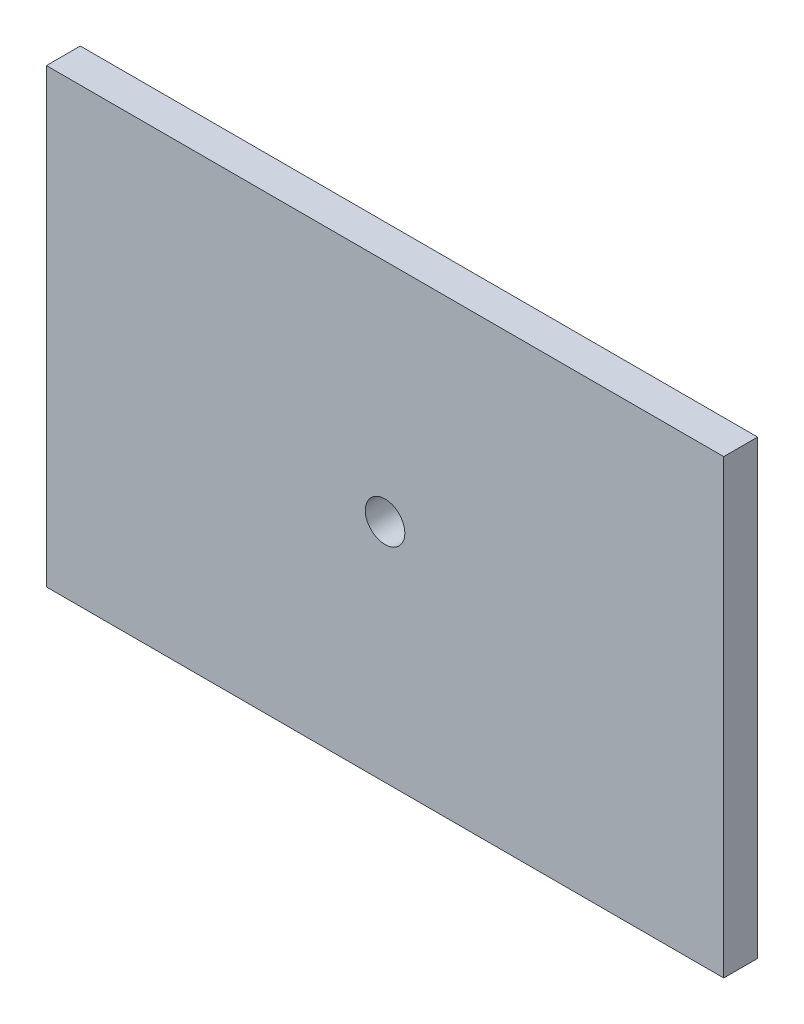
SolidWorks part; units mm, degrees
ref_plane "Alzado" through (0, 0, 0) normal (0, 0, 1) x (1, 0, 0)
ref_plane "Planta" through (0, 0, 0) normal (0, 1, 0) x (1, 0, 0)
ref_plane "Vista lateral" through (0, 0, 0) normal (1, 0, 0) x (0, 0, -1)
sketch "Sketch1" plane through (0, 0, 0) normal (0, 0, 1) x (1, 0, 0)
  line L1 (60, -40) -> (-60, -40)
  line L2 (60, -40) -> (60, 40)
  line L3 (60, 40) -> (-60, 40)
  line L4 (-60, -40) -> (-60, 40)
  line L5 (60, -40) -> (-60, 40) construction
  line L6 (60, 40) -> (-60, -40) construction
  point P0 (0, 0)
  dimension "D1" = 80
  dimension "D2" = 120
extrude "Boss-Extrude1" add sketch "Sketch1" along normal blind 6
sketch "Sketch2" plane through (0, 0, 0) normal (0, 0, 1) x (1, 0, 0)
  circle A0 centre (0, 0) radius 3.5
extrude "Cut-Extrude3" cut sketch "Sketch2" along direction (0, 0, 1) on the side against the normal through all and the other way through all
